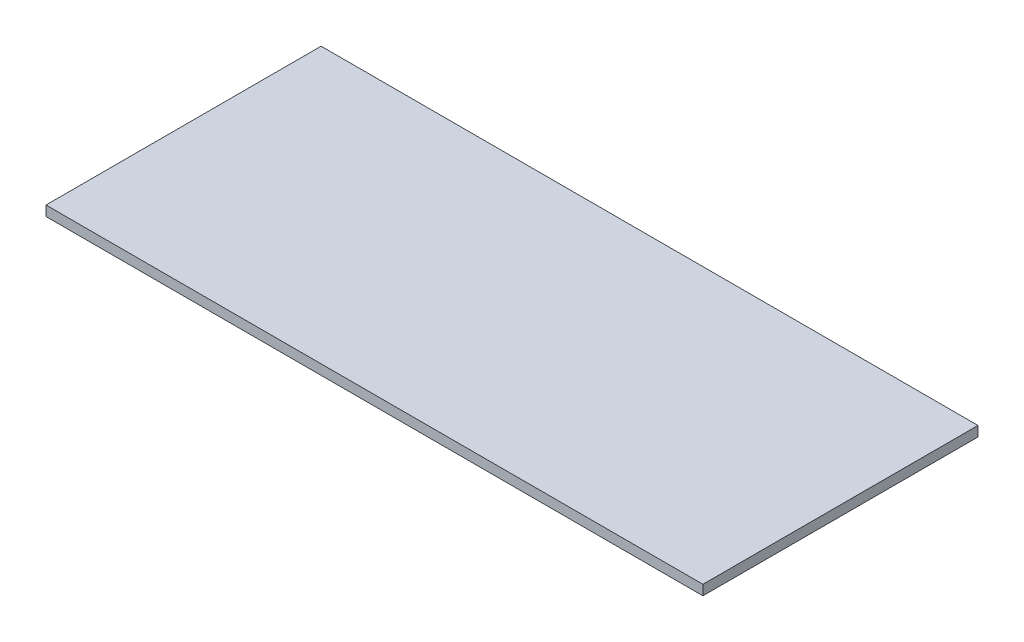
SolidWorks part; units mm, degrees
ref_plane "Front" through (0, 0, 0) normal (0, 0, 1) x (1, 0, 0)
ref_plane "Top" through (0, 0, 0) normal (0, 1, 0) x (1, 0, 0)
ref_plane "Right" through (0, 0, 0) normal (1, 0, 0) x (0, 0, -1)
sketch "Эскиз1" plane through (0, 0, 0) normal (0, 1, 0) x (1, 0, 0)
  line L1 (103, 167) -> (497, 167)
  line L2 (103, 167) -> (103, 2)
  line L3 (103, 2) -> (497, 2)
  line L4 (497, 167) -> (497, 2)
  dimension "D1" = 165
  dimension "D2" = 394
extrude "Бобышка-Вытянуть1" add sketch "Эскиз1" along normal blind 6
